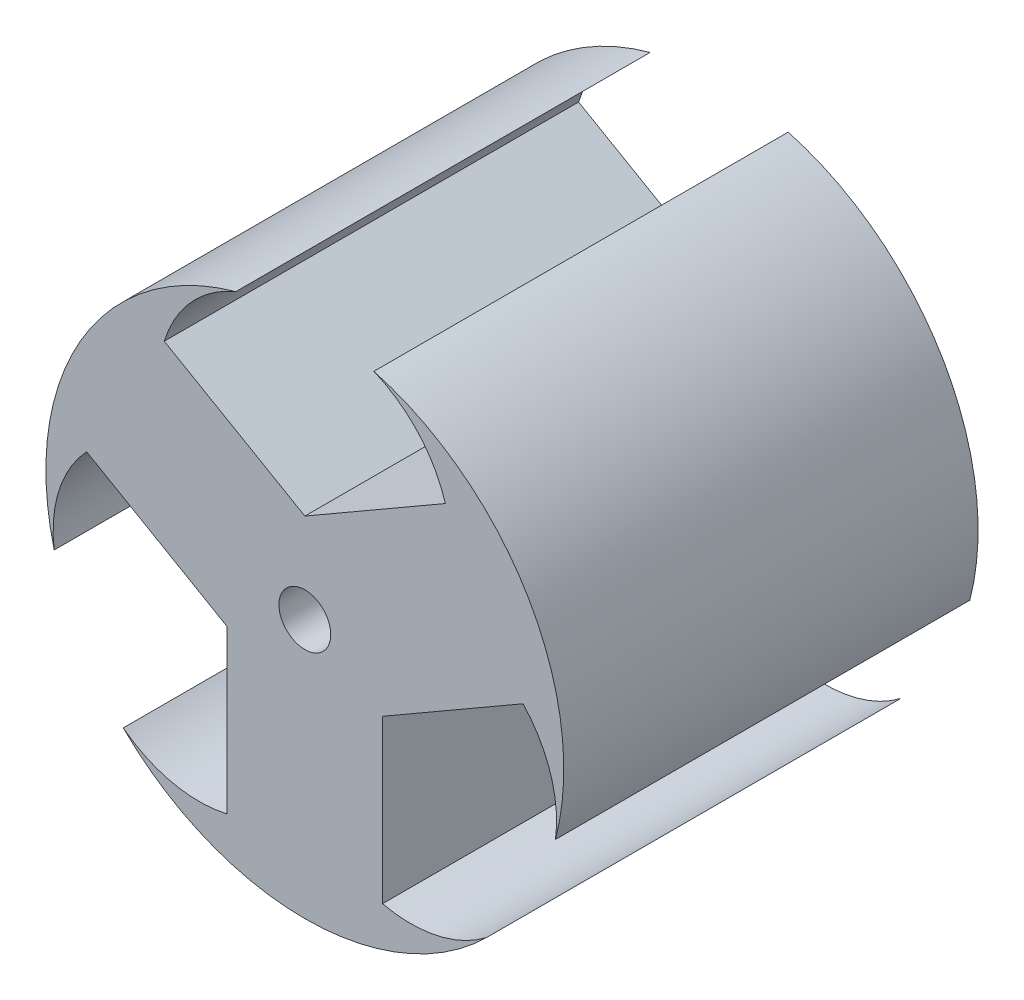
SolidWorks part; units mm, degrees
ref_plane "Front Plane" through (0, 0, 0) normal (0, 0, 1) x (1, 0, 0)
ref_plane "Top Plane" through (0, 0, 0) normal (0, 1, 0) x (1, 0, 0)
ref_plane "Right Plane" through (0, 0, 0) normal (1, 0, 0) x (0, 0, -1)
sketch "Sketch1" plane through (0, 0, 0) normal (0, 0, 1) x (1, 0, 0)
  line L0 (0, 34.5078) -> (0, 25) construction
  line L2 (-7.5, 0) -> (-7.5, -20)
  line L4 (7.5, 0) -> (7.5, -20)
  line L5 (-3.75, -6.4952) -> (-21.0705, 3.5048)
  line L6 (3.75, 6.4952) -> (-13.5705, 16.4952)
  line L7 (-3.75, 6.4952) -> (13.5705, 16.4952)
  line L8 (3.75, -6.4952) -> (21.0705, 3.5048)
  circle A0 centre (0, 0) radius 2.5
  arc A2 (-17.5357, -17.8185) -> (17.5357, -17.8185) centre (0, 0) ccw
  arc A3 (-7.5, -20) -> (-17.5357, -17.8185) centre (-10.2042, -8.2657) cw
  arc A4 (7.5, -20) -> (17.5357, -17.8185) centre (10.2042, -8.2657) ccw
  arc A5 (7.5, 0) -> (-7.5, 0) centre (0, 0) ccw
  arc A6 (-3.75, -6.4952) -> (3.75, 6.4952) centre (0, 0) ccw
  arc A7 (-13.5705, 16.4952) -> (-6.6634, 24.0956) centre (-2.0562, 12.97) cw
  arc A8 (-6.6634, 24.0956) -> (-24.1991, -6.2771) centre (0, 0) ccw
  arc A9 (-21.0705, 3.5048) -> (-24.1991, -6.2771) centre (-12.2604, -4.7043) ccw
  arc A10 (-3.75, 6.4952) -> (3.75, -6.4952) centre (0, 0) ccw
  arc A11 (21.0705, 3.5048) -> (24.1991, -6.2771) centre (12.2604, -4.7043) cw
  arc A12 (24.1991, -6.2771) -> (6.6634, 24.0956) centre (0, 0) ccw
  arc A13 (13.5705, 16.4952) -> (6.6634, 24.0956) centre (2.0562, 12.97) ccw
  point P32 (0, 0)
  dimension "D1" = 5
  dimension "D2" = 3
  dimension "D5" = 50
  dimension "D3" = 15
  dimension "D4" = 20
extrude "Boss-Extrude1" add sketch "Sketch1" along normal blind 40 contours A9 L5 L2 A5 L7 L6 A7 A8 | A13 L7 L6 A5 L4 L8 A11 A12 | A6 L5 L2 A3 A2 A4 L4 L8 | A5 L6 L7 | A10 L2 L5 | A6 L8 L4 | A5 A10 A6 A0
